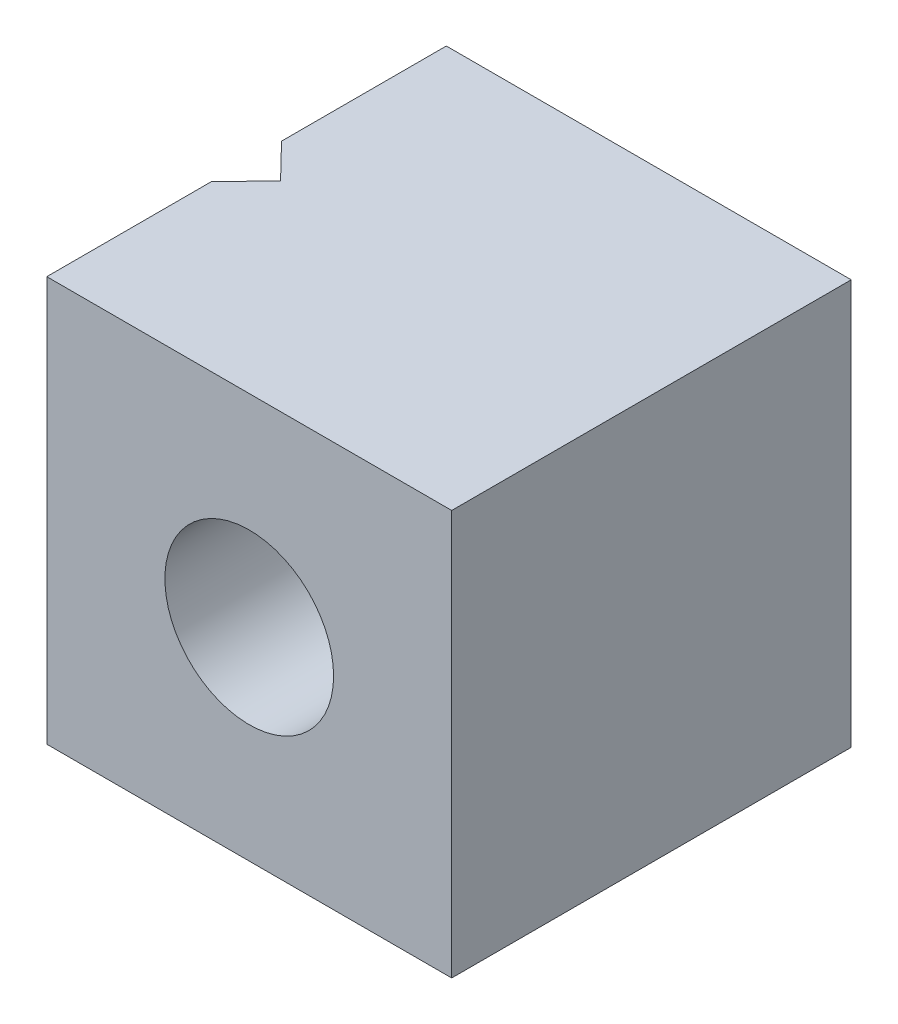
SolidWorks part; units mm, degrees
ref_plane "Front Plane" through (0, 0, 0) normal (0, 0, 1) x (1, 0, 0)
ref_plane "Top Plane" through (0, 0, 0) normal (0, 1, 0) x (1, 0, 0)
ref_plane "Right Plane" through (0, 0, 0) normal (1, 0, 0) x (0, 0, -1)
sketch "Sketch1" plane through (0, 0, 0) normal (0, 0, 1) x (1, 0, 0)
  line L0 (0, 0) -> (19.05, -19.05) construction
  line L1 (0, 0) -> (19.05, 0)
  line L2 (0, 0) -> (0, -19.05)
  line L3 (0, -19.05) -> (19.05, -19.05)
  line L4 (19.05, 0) -> (19.05, -19.05)
  circle A0 centre (9.525, -9.525) radius 3.9687
  dimension "D3" = 7.9375
  dimension "D1" = 19.05
  dimension "D2" = 19.05
extrude "Boss-Extrude1" add sketch "Sketch1" against normal blind 18.796
sketch "Sketch2" plane through (0, 0, 0) normal (0, 1, 0) x (1, 0, 0)
  line L0 (0, 0) -> (0, 18.796) construction
  line L1 (19.05, 9.398) -> (0, 9.398) construction
  line L2 (19.05, 18.796) -> (19.05, 0) construction
  line L3 (0, 7.7516) -> (1.6002, 9.398)
  line L4 (1.6002, 9.398) -> (0, 11.0444)
  line L5 (0, 11.0444) -> (0, 7.7516)
  point P10 (0, 0)
  point P12 (0, 9.398)
  dimension "D1" = 91.63
  dimension "D3" = 1.6002
extrude "Cut-Extrude1" cut sketch "Sketch2" against normal through all and the other way through all
